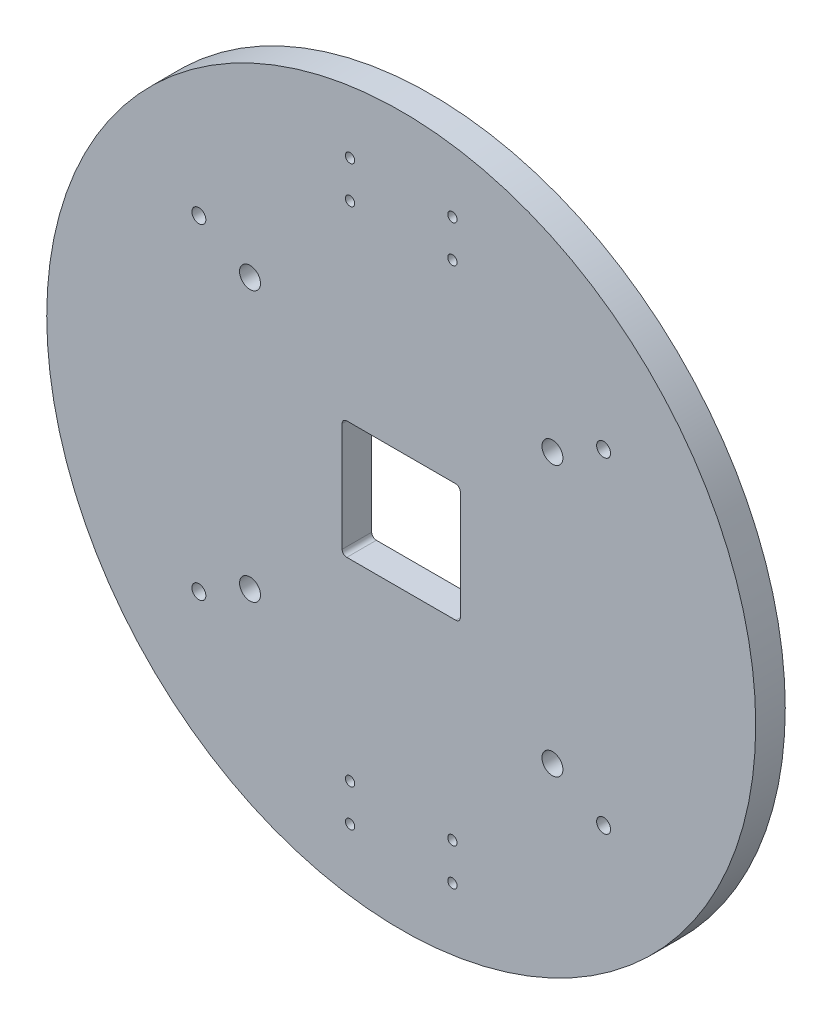
SolidWorks part; units mm, degrees
ref_plane "Front Plane" through (0, 0, 0) normal (0, 0, 1) x (1, 0, 0)
ref_plane "Top Plane" through (0, 0, 0) normal (0, 1, 0) x (1, 0, 0)
ref_plane "Right Plane" through (0, 0, 0) normal (1, 0, 0) x (0, 0, -1)
sketch "Sketch1" plane through (0, 0, 0) normal (0, 0, 1) x (1, 0, 0)
  line L0 (0, 0) -> (0, -58) construction
  line L1 (43.5, 35) -> (-43.5, 35) construction
  line L2 (43.5, 35) -> (43.5, -35) construction
  line L3 (43.5, -35) -> (-43.5, -35) construction
  line L4 (-43.5, 35) -> (-43.5, -35) construction
  line L5 (43.5, 35) -> (-43.5, -35) construction
  line L6 (43.5, -35) -> (-43.5, 35) construction
  line L7 (-32.5, 29) -> (32.5, 29) construction
  line L8 (-32.5, 29) -> (-32.5, -29) construction
  line L9 (-32.5, -29) -> (32.5, -29) construction
  line L10 (32.5, 29) -> (32.5, -29) construction
  line L11 (-32.5, 29) -> (32.5, -29) construction
  line L12 (-32.5, -29) -> (32.5, 29) construction
  line L17 (12.7, 11.3323) -> (-15.7655, -14.0677) construction
  line L18 (12.7, 12.7) -> (-12.7, 12.7)
  line L19 (12.7, 12.7) -> (12.7, -12.7)
  line L20 (12.7, -12.7) -> (-12.7, -12.7)
  line L21 (-12.7, 12.7) -> (-12.7, -12.7)
  line L22 (12.7, 12.7) -> (-12.7, -12.7) construction
  line L23 (12.7, -12.7) -> (-12.7, 12.7) construction
  line L24 (0, 0) -> (0, 58) construction
  line L26 (-11, -62) -> (11, -62) construction
  line L27 (-11, -62) -> (-11, -54) construction
  line L28 (-11, -54) -> (11, -54) construction
  line L29 (11, -62) -> (11, -54) construction
  line L30 (-11, -62) -> (11, -54) construction
  line L31 (-11, -54) -> (11, -62) construction
  line L32 (-11, 54) -> (11, 54) construction
  line L33 (-11, 54) -> (-11, 62) construction
  line L34 (-11, 62) -> (11, 62) construction
  line L35 (11, 54) -> (11, 62) construction
  line L36 (-11, 54) -> (11, 62) construction
  line L37 (-11, 62) -> (11, 54) construction
  circle A0 centre (0, 0) radius 76.2
  circle A2 centre (-32.5, 29) radius 2.25
  circle A3 centre (-32.5, -29) radius 2.25
  circle A4 centre (32.5, -29) radius 2.25
  circle A5 centre (32.5, 29) radius 2.25
  circle A6 centre (43.5, 35) radius 1.5
  circle A7 centre (-43.5, 35) radius 1.5
  circle A8 centre (43.5, -35) radius 1.5
  circle A9 centre (-43.5, -35) radius 1.5
  circle A10 centre (-11, 54) radius 1
  circle A11 centre (11, 54) radius 1
  circle A12 centre (11, 62) radius 1
  circle A13 centre (-11, 62) radius 1
  circle A14 centre (-11, -62) radius 1
  circle A15 centre (-11, -54) radius 1
  circle A16 centre (11, -62) radius 1
  circle A17 centre (11, -54) radius 1
  dimension "D1" = 152.4
  dimension "D8" = 4.5
  dimension "D9" = 4.5
  dimension "D10" = 4.5
  dimension "D11" = 4.5
  dimension "D12" = 3
  dimension "D13" = 3
  dimension "D14" = 3
  dimension "D15" = 3
  dimension "D2" = 87
  dimension "D3" = 70
  dimension "D4" = 65
  dimension "D5" = 58
  dimension "D6" = 25.4
  dimension "D7" = 25.4
  dimension "D16" = 58
extrude "Boss-Extrude2" add sketch "Sketch1" along normal blind 6.35
fillet "Fillet3" radius 1 1 edges at (-12.7, -12.7, 3.175)
fillet "Fillet4" radius 1 1 edges at (12.7, 12.7, 3.175)
fillet "Fillet5" radius 1 1 edges at (-12.7, 12.7, 3.175)
fillet "Fillet6" radius 1 1 edges at (12.7, -12.7, 3.175)
